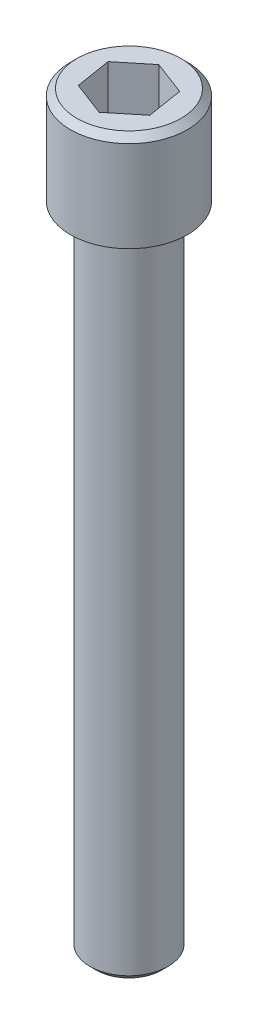
SolidWorks part; units mm, degrees
ref_plane "Přední rovina" through (0, 0, 0) normal (0, 0, 1) x (1, 0, 0)
ref_plane "Horní rovina" through (0, 0, 0) normal (0, 1, 0) x (1, 0, 0)
ref_plane "Pravá rovina" through (0, 0, 0) normal (1, 0, 0) x (0, 0, -1)
sketch "Skica1" plane through (0, 0, 0) normal (0, 1, 0) x (1, 0, 0)
  circle A0 centre (0, 0) radius 1.5
  dimension "D1" = 3
extrude "Přidat vysunutím1" add sketch "Skica1" along normal blind 25
sketch "Skica2" plane through (0, 25, 0) normal (0, 1, 0) x (1, 0, 0)
  circle A0 centre (0, 0) radius 2.25
  dimension "D1" = 4.5
extrude "Přidat vysunutím2" add sketch "Skica2" along normal blind 3.75
sketch "Skica3" plane through (0, 28.75, 0) normal (0, 1, 0) x (1, 0, 0)
  line L1 (-1.0744, -0.875) -> (0.2206, -1.368)
  line L2 (0.2206, -1.368) -> (1.295, -0.493)
  line L3 (1.295, -0.493) -> (1.0744, 0.875)
  line L4 (1.0744, 0.875) -> (-0.2206, 1.368)
  line L5 (-0.2206, 1.368) -> (-1.295, 0.493)
  line L6 (-1.295, 0.493) -> (-1.0744, -0.875)
  circle A0 centre (0, 0) radius 1.2 construction
  dimension "D1" = 2.4
extrude "Odebrat vysunutím1" cut sketch "Skica3" against normal blind 2.25
chamfer "Zkosení1" distance 0.25 angle 45 1 edges at (0, 28.75, 2.25)
chamfer "Zkosení2" distance 0.25 angle 45 1 edges at (0, 0, 1.5)
